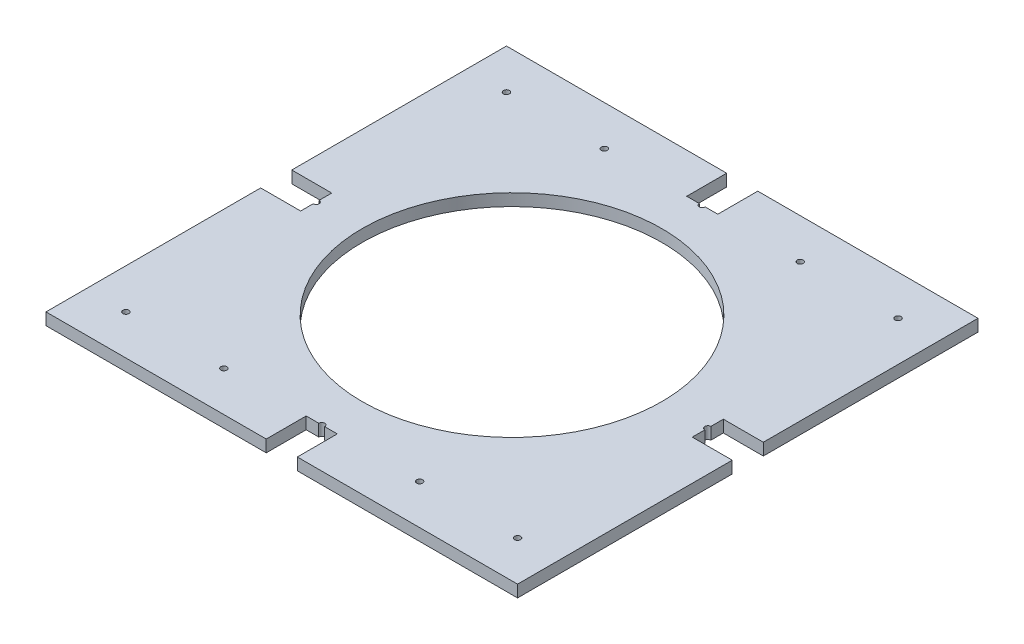
SolidWorks part; units mm, degrees
ref_plane "前视基准面" through (0, 0, 0) normal (0, 0, 1) x (1, 0, 0)
ref_plane "上视基准面" through (0, 0, 0) normal (0, 1, 0) x (1, 0, 0)
ref_plane "右视基准面" through (0, 0, 0) normal (1, 0, 0) x (0, 0, -1)
sketch "草图1" plane through (0, 0, 0) normal (0, 1, 0) x (1, 0, 0)
  line L0 (-128, -85.225) -> (8.2905, -85.225) construction
  line L1 (-128, 125.225) -> (-17.78, 125.225)
  line L2 (-128, 125.225) -> (-128, 17.78)
  line L3 (-128, -105.225) -> (-17.78, -105.225)
  line L4 (108, 125.225) -> (108, 17.78)
  line L5 (-128, 105.225) -> (-11.5, 105.225) construction
  line L6 (-108, 125.225) -> (-108, 11.5) construction
  line L8 (88, 125.225) -> (88, 11.5) construction
  line L9 (-108, 15) -> (-108, 11.5)
  line L11 (-128, 2.22) -> (-128, -105.225)
  line L12 (-108, 8.5) -> (-108, -105.225) construction
  line L13 (-108, 8.5) -> (-108, 5)
  line L15 (-15, 105.225) -> (-11.5, 105.225)
  line L17 (-2.22, 125.225) -> (108, 125.225)
  line L18 (-8.5, 105.225) -> (108, 105.225) construction
  line L19 (-8.5, 105.225) -> (-5, 105.225)
  line L20 (-10, 125.225) -> (-10, -105.225) construction
  line L21 (-128, 10) -> (88, 10) construction
  line L26 (-15, -85.225) -> (-11.5, -85.225)
  line L27 (-2.22, -105.225) -> (108, -105.225)
  line L28 (-8.5, -85.225) -> (108, -85.225) construction
  line L29 (-8.5, -85.225) -> (-5, -85.225)
  line L30 (88, 15) -> (88, 11.5)
  line L31 (108, 2.22) -> (108, -105.225)
  line L32 (88, 8.5) -> (88, -105.225) construction
  line L33 (88, 8.5) -> (88, 5)
  line L34 (-15, -85.225) -> (-17.78, -85.225)
  line L35 (-17.78, -85.225) -> (-17.78, -105.225)
  line L36 (-5, -85.225) -> (-2.22, -85.225)
  line L37 (-2.22, -85.225) -> (-2.22, -105.225)
  line L38 (-5, 105.225) -> (-2.22, 105.225)
  line L39 (-2.22, 105.225) -> (-2.22, 125.225)
  line L40 (-15, 105.225) -> (-17.78, 105.225)
  line L41 (-17.78, 105.225) -> (-17.78, 125.225)
  line L42 (-108, 15) -> (-108, 17.78)
  line L43 (-108, 17.78) -> (-128, 17.78)
  line L44 (-108, 5) -> (-108, 2.22)
  line L45 (-108, 2.22) -> (-128, 2.22)
  line L46 (88, 15) -> (88, 17.78)
  line L47 (88, 17.78) -> (108, 17.78)
  line L48 (88, 5) -> (88, 2.22)
  line L49 (88, 2.22) -> (108, 2.22)
  circle A0 centre (-108, 105.225) radius 1.5
  circle A1 centre (-59, 105.225) radius 1.5
  arc A2 (-11.5, 105.225) -> (-8.5, 105.225) centre (-10, 105.225) ccw
  circle A3 centre (39, 105.225) radius 1.5
  circle A4 centre (88, 105.225) radius 1.5
  circle A5 centre (-108, -85.225) radius 1.5
  arc A6 (-108, 8.5) -> (-108, 11.5) centre (-108, 10) ccw
  arc A7 (88, 11.5) -> (88, 8.5) centre (88, 10) ccw
  circle A8 centre (-59, -85.225) radius 1.5
  arc A9 (-8.5, -85.225) -> (-11.5, -85.225) centre (-10, -85.225) ccw
  circle A10 centre (39, -85.225) radius 1.5
  circle A11 centre (88, -85.225) radius 1.5
  circle A12 centre (-10, 10) radius 75
  dimension "D8" = 3
  dimension "D10" = 3
  dimension "D11" = 3
  dimension "D12" = 3
  dimension "D20" = 150
  dimension "D1" = 236
  dimension "D2" = 230.45
  dimension "D3" = 128
  dimension "D4" = 125.225
  dimension "D5" = 20
  dimension "D6" = 20
  dimension "D7" = 20
  dimension "D9" = 5
  dimension "D14" = 20
  dimension "D15" = 7.78
  dimension "D16" = 7.78
  dimension "D17" = 7.78
  dimension "D18" = 49
  dimension "D19" = 7.78
  dimension "D21" = 7.78
  dimension "D22" = 7.78
  dimension "D23" = 7.78
  dimension "D24" = 7.78
  dimension "D13" = 5
extrude "凸台-拉伸1" add sketch "草图1" along normal blind 6
